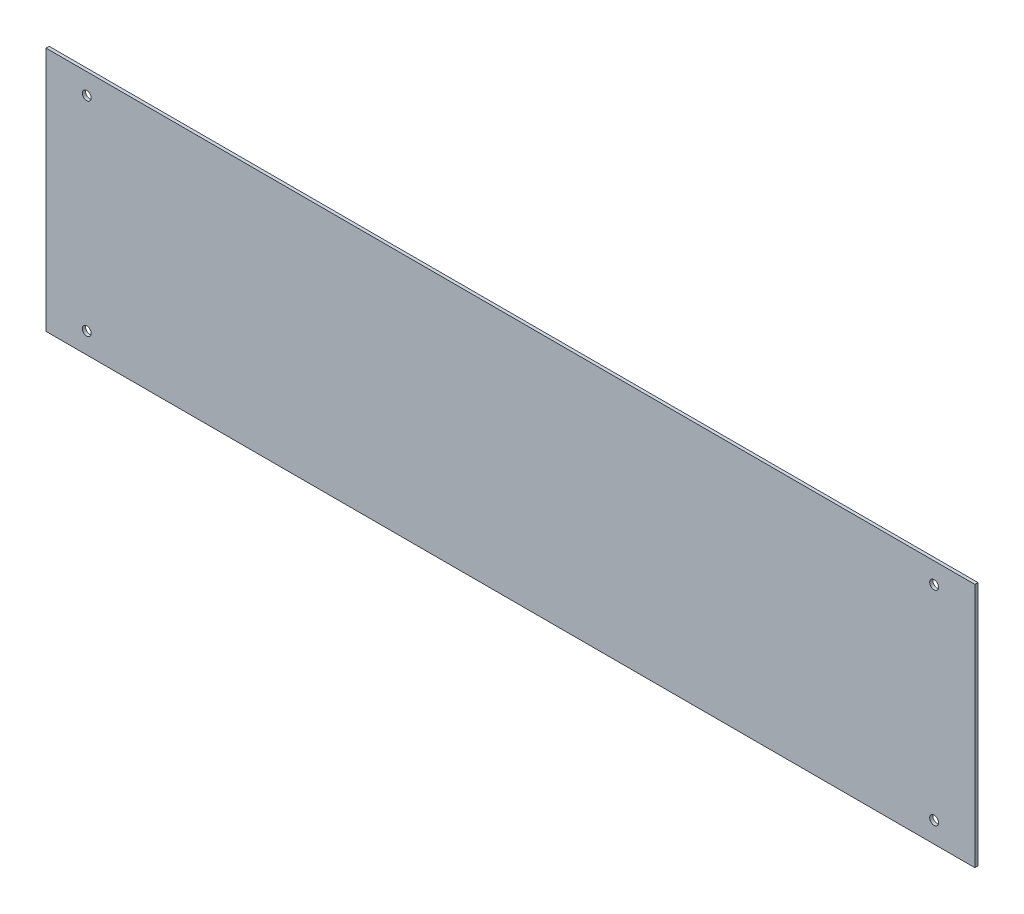
SolidWorks part; units mm, degrees
material "ABS"
ref_plane "X-Y Datum" through (0, 0, 0) normal (0, 0, 1) x (1, 0, 0)
ref_plane "X-Z Datum" through (0, 0, 0) normal (0, 1, 0) x (1, 0, 0)
ref_plane "Y-Z Datum" through (0, 0, 0) normal (1, 0, 0) x (0, 0, -1)
sketch "Sketch1" plane through (0, 0, 0) normal (0, 0, 1) x (1, 0, 0)
  line L1 (15.0366, -280.2154) -> (485.8706, -280.2154)
  line L2 (15.0366, -280.2154) -> (15.0366, -404.5934)
  line L3 (15.0366, -404.5934) -> (485.8706, -404.5934)
  line L4 (485.8706, -280.2154) -> (485.8706, -404.5934)
  circle A0 centre (465.2106, -290.7254) radius 1.3492
  circle A1 centre (465.2106, -394.0834) radius 1.283
  circle A2 centre (35.6966, -290.7254) radius 1.3697
  circle A3 centre (35.6966, -394.0834) radius 1.4844
extrude "Boss-Extrude1" add sketch "Sketch1" along normal blind 1.5875
hole_wizard "M4 Clearance Hole1" positions "Sketch2" profile "Sketch3" hole size "M4" standard "ANSI Metric" end condition through all
sketch "Sketch2" plane through (0, 0, 1.5875) normal (0, 0, 1) x (1, 0, 0)
  point P0 (35.6966, -290.7254)
  point P3 (35.6966, -394.0834)
  point P6 (465.2106, -290.7254)
  point P9 (465.2106, -394.0834)
sketch "Sketch3" plane through (35.6966, -290.7254, 1.5875) normal (1, 0, 0) x (0, -1, 0)
  line L0 (0, 0) -> (0, 1.5875)
  line L1 (0, 1.5875) -> (2.25, 1.5875)
  line L2 (2.25, 1.5875) -> (2.25, 0)
  line L5 (2.25, 0) -> (0, 0)
  line L11 (0, -6.35) -> (0, 107.95) construction
  dimension "Thru Hole Dia." = 4.5
  dimension "Thru Hole Depth" = 1.5875
